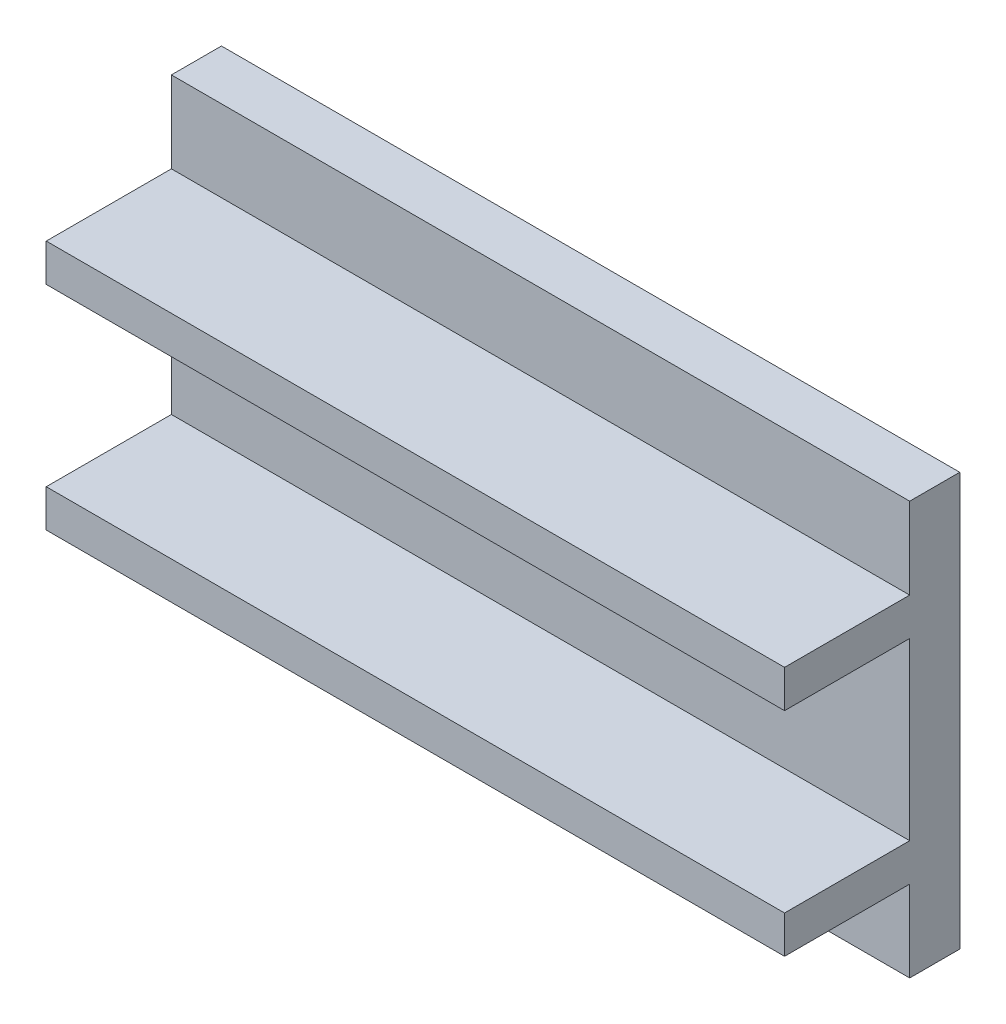
SolidWorks part; units mm, degrees
ref_plane "Płaszczyzna przednia" through (0, 0, 0) normal (0, 0, 1) x (1, 0, 0)
ref_plane "Płaszczyzna górna" through (0, 0, 0) normal (0, 1, 0) x (1, 0, 0)
ref_plane "Płaszczyzna prawa" through (0, 0, 0) normal (1, 0, 0) x (0, 0, -1)
sketch "Szkic1" plane through (0, 0, 0) normal (0, 0, 1) x (1, 0, 0)
  line L1 (-14.75, 8.25) -> (14.75, 8.25)
  line L2 (-14.75, 8.25) -> (-14.75, -8.25)
  line L3 (-14.75, -8.25) -> (14.75, -8.25)
  line L4 (14.75, 8.25) -> (14.75, -8.25)
  line L5 (-14.75, 8.25) -> (14.75, -8.25) construction
  line L6 (-14.75, -8.25) -> (14.75, 8.25) construction
  point P0 (0, 0)
  dimension "D1" = 16.5
  dimension "D2" = 29.5
extrude "Dodanie-wyciągnięcie1" add sketch "Szkic1" along normal blind 2
sketch "Szkic2" plane through (0, 0, 2) normal (0, 0, 1) x (1, 0, 0)
  line L0 (-14.75, 8.25) -> (-14.75, -8.25) construction
  line L1 (14.75, -3.5) -> (-14.75, -3.5)
  line L2 (14.75, -3.5) -> (14.75, 3.5)
  line L3 (14.75, 3.5) -> (-14.75, 3.5)
  line L4 (-14.75, -3.5) -> (-14.75, 3.5)
  line L5 (14.75, -3.5) -> (-14.75, 3.5) construction
  line L6 (14.75, 3.5) -> (-14.75, -3.5) construction
  line L8 (14.75, -5) -> (-14.75, -5)
  line L9 (14.75, -5) -> (14.75, 5)
  line L10 (14.75, 5) -> (-14.75, 5)
  line L11 (-14.75, -5) -> (-14.75, 5)
  line L12 (14.75, -5) -> (-14.75, 5) construction
  line L13 (14.75, 5) -> (-14.75, -5) construction
  point P0 (0, 0)
  point P8 (0, 0)
  line M4 (14.75, -8.25) -> (14.75, 8.25)
  line M6 (-14.75, 8.25) -> (-14.75, -8.25)
  dimension "D1" = 1.5
  dimension "D2" = 7
extrude "Dodanie-wyciągnięcie2" add sketch "Szkic2" along normal blind 5 contours L10 L3 M4 M6 | L8 L1 M4 M6
